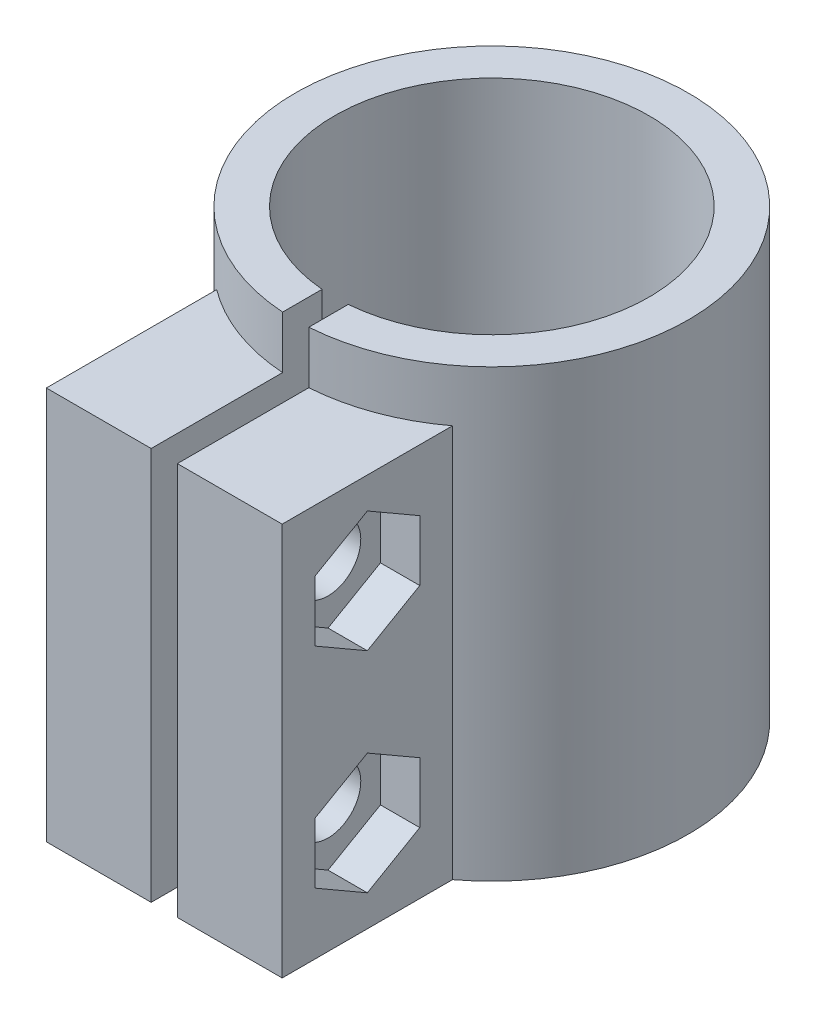
SolidWorks part; units mm, degrees
ref_plane "前视基准面" through (0, 0, 0) normal (0, 0, 1) x (1, 0, 0)
ref_plane "上视基准面" through (0, 0, 0) normal (0, 1, 0) x (1, 0, 0)
ref_plane "右视基准面" through (0, 0, 0) normal (1, 0, 0) x (0, 0, -1)
sketch "草图1" plane through (0, 0, 0) normal (0, 1, 0) x (1, 0, 0)
  circle A0 centre (0, 0) radius 6
  circle A1 centre (0, 0) radius 7.5
  dimension "D1" = 12
  dimension "D2" = 15
extrude "凸台-拉伸1" add sketch "草图1" along normal blind 17
ref_plane "基准面1" through (0, 0, 7.5) normal (0, 0, 1) x (1, 0, 0)
sketch "草图2" plane through (0, 0, 7.5) normal (0, 0, 1) x (1, 0, 0)
  line L0 (0, 0) -> (0, 17) construction
  line L1 (6, 17) -> (-6, 17) construction
  line L2 (-7.5, 0) -> (7.5, 0) construction
  line L3 (-0.5, 17) -> (0.5, 17)
  line L4 (-0.5, 17) -> (-0.5, 0)
  line L5 (-0.5, 0) -> (0.5, 0)
  line L6 (0.5, 17) -> (0.5, 0)
  line L7 (-0.5, 17) -> (0.5, 0) construction
  line L8 (-0.5, 0) -> (0.5, 17) construction
  point P5 (0, 8.5)
  dimension "D1" = 1
extrude "切除-拉伸1" cut sketch "草图2" against normal up to next
sketch "草图3" plane through (0, 0, 7.5) normal (0, 0, 1) x (1, 0, 0)
  line L0 (-7.5, 0) -> (7.5, 0) construction
  line L1 (-0.5, 17) -> (-4.5, 17)
  line L2 (-0.5, 17) -> (-0.5, 0)
  line L3 (-0.5, 0) -> (-4.5, 0)
  line L4 (-4.5, 17) -> (-4.5, 0)
  line L6 (0.5, 17) -> (4.5, 17)
  line L7 (0.5, 17) -> (0.5, 0)
  line L8 (0.5, 0) -> (4.5, 0)
  line L9 (4.5, 17) -> (4.5, 0)
  dimension "D1" = 4
extrude "凸台-拉伸2" add sketch "草图3" along normal blind 5 and the other way up to next
sketch "草图7" plane through (0, 17, 0) normal (0, 1, 0) x (1, 0, 0)
  line L0 (-4.5, -6) -> (-4.5, -12.5)
  line L1 (-4.5, -12.5) -> (4.5, -12.5)
  line L2 (4.5, -12.5) -> (4.5, -6)
  arc A0 (-4.5, -6) -> (4.5, -6) centre (0, 0) ccw
extrude "切除-拉伸4" cut sketch "草图7" against normal blind 2
sketch "草图4" plane through (-4.5, 0, 0) normal (-1, 0, 0) x (0, 0, 1)
  line L0 (6, 7.5) -> (12.5, 7.5) construction
  line L1 (6, 15) -> (6, 0) construction
  line L2 (12.5, 15) -> (12.5, 0) construction
  line L3 (9.25, 11.5) -> (9.25, 3.5) construction
  circle A0 centre (9.25, 11.5) radius 1.25
  circle A1 centre (9.25, 3.5) radius 1.25
  point P9 (9.25, 7.5)
  dimension "D2" = 2.5
  dimension "D1" = 8
extrude "切除-拉伸2" cut sketch "草图4" against normal up to surface (9 mm away) up to face at (4.5, 7.5, 9.25)
sketch "草图5" plane through (4.5, 0, 0) normal (1, 0, 0) x (0, 0, -1)
  line L1 (-9.25, 9.1906) -> (-7.25, 10.3453)
  line L2 (-7.25, 10.3453) -> (-7.25, 12.6547)
  line L3 (-7.25, 12.6547) -> (-9.25, 13.8094)
  line L4 (-9.25, 13.8094) -> (-11.25, 12.6547)
  line L5 (-11.25, 12.6547) -> (-11.25, 10.3453)
  line L6 (-11.25, 10.3453) -> (-9.25, 9.1906)
  line L7 (-9.25, 1.1906) -> (-7.25, 2.3453)
  line L8 (-7.25, 2.3453) -> (-7.25, 4.6547)
  line L9 (-7.25, 4.6547) -> (-9.25, 5.8094)
  line L10 (-9.25, 5.8094) -> (-11.25, 4.6547)
  line L11 (-11.25, 4.6547) -> (-11.25, 2.3453)
  line L12 (-11.25, 2.3453) -> (-9.25, 1.1906)
  circle A0 centre (-9.25, 11.5) radius 2 construction
  circle A1 centre (-9.25, 3.5) radius 2 construction
  dimension "D1" = 4
extrude "切除-拉伸3" cut sketch "草图5" against normal blind 1.5
